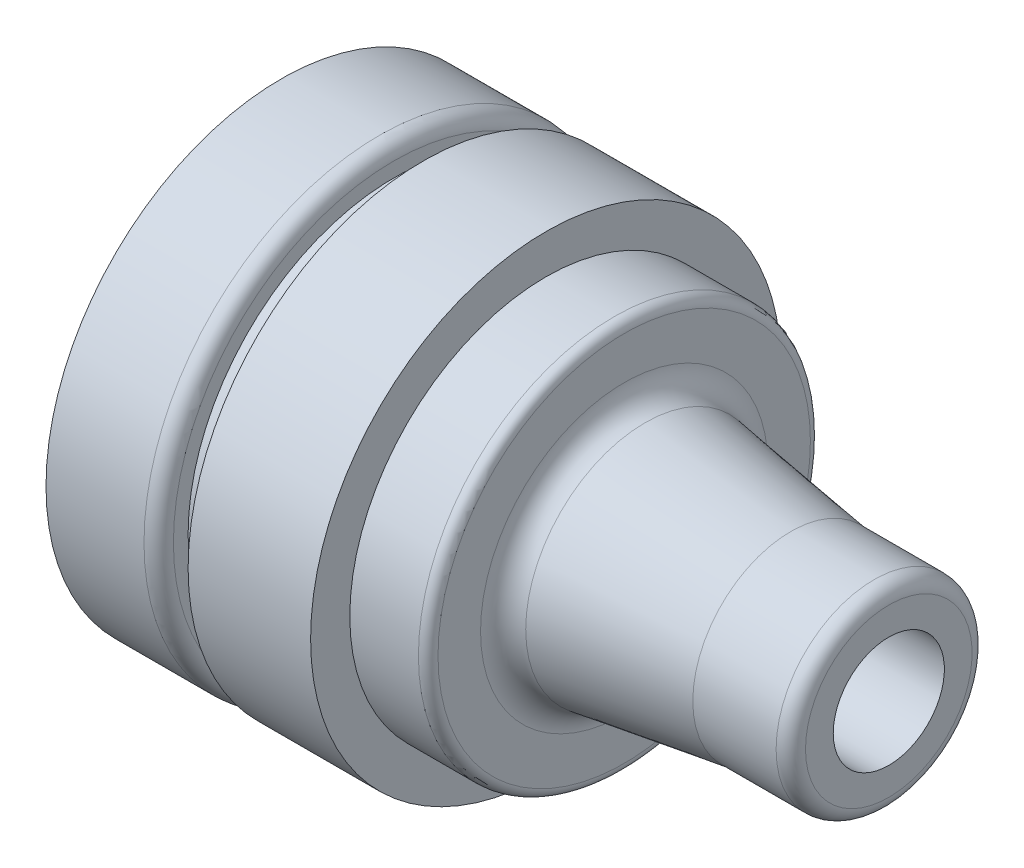
SolidWorks part; units mm, degrees
ref_plane "Front Plane" through (0, 0, 0) normal (0, 0, 1) x (1, 0, 0)
ref_plane "Top Plane" through (0, 0, 0) normal (0, 1, 0) x (1, 0, 0)
ref_plane "Right Plane" through (0, 0, 0) normal (1, 0, 0) x (0, 0, -1)
sketch "Sketch1" plane through (0, 0, 0) normal (0, 0, 1) x (1, 0, 0)
  line L0 (0, 0) -> (115.0408, 0)
  line L1 (0, 0) -> (0, 19.085)
  line L2 (0, 19.085) -> (57.5204, 19.085)
  line L3 (57.5204, 19.085) -> (57.5204, 0)
  line L4 (57.5204, 11.339) -> (115.0408, 11.339)
  line L5 (115.0408, 11.339) -> (115.0408, 0)
  line L6 (115.0408, 11.339) -> (115.0408, 17)
  line L7 (95.0408, 20) -> (112.0408, 20)
  line L8 (95.0408, 20) -> (95.0408, 11.339)
  line L9 (57.5204, 19.085) -> (28.5575, 19.085)
  line L10 (95.0408, 20) -> (65.3133, 24.3717)
  line L11 (54.1867, 40) -> (45.0408, 40)
  line L12 (45.0408, 40) -> (45.0408, 48)
  line L13 (45.0408, 48) -> (20.0408, 48)
  line L14 (20.0408, 48) -> (20.0408, 42)
  line L15 (20.0408, 42) -> (14.0408, 42)
  line L16 (14.0408, 42) -> (14.0408, 45)
  line L17 (11.0408, 48) -> (-8.9592, 48)
  line L18 (-8.9592, 48) -> (-8.9592, 38)
  line L19 (-8.9592, 38) -> (0, 19.085)
  line L20 (14.0408, 42) -> (14.0408, 19.085)
  line L21 (20.0408, 42) -> (20.0408, 19.085)
  line L22 (45.0408, 40) -> (45.0408, 19.085)
  line L24 (61.0408, 29.3185) -> (61.0408, 38)
  line L25 (59.0408, 40) -> (54.1867, 40)
  arc A0 (112.0408, 20) -> (115.0408, 17) centre (112.0408, 17) cw
  arc A1 (65.3133, 24.3717) -> (61.0408, 29.3185) centre (66.0408, 29.3185) cw
  arc A2 (14.0408, 45) -> (11.0408, 48) centre (11.0408, 45) ccw
  arc A3 (61.0408, 38) -> (59.0408, 40) centre (59.0408, 38) ccw
  point P26 (115.0408, 20)
  point P31 (61.0408, 25)
  point P36 (61.0408, 40)
  dimension "D3" = 3
  dimension "D4" = 15
  dimension "D15" = 3
  dimension "D16" = 5
  dimension "D18" = 2
  dimension "D1" = 19.085
  dimension "D2" = 20
  dimension "D5" = 124
  dimension "D6" = 20
  dimension "D7" = 54
  dimension "D8" = 70
  dimension "D9" = 48
  dimension "D10" = 25
  dimension "D11" = 6
  dimension "D12" = 42
  dimension "D13" = 48
  dimension "D14" = 10
  dimension "D17" = 40
revolve "Revolve1" add sketch "Sketch1" angle 360 about L0
